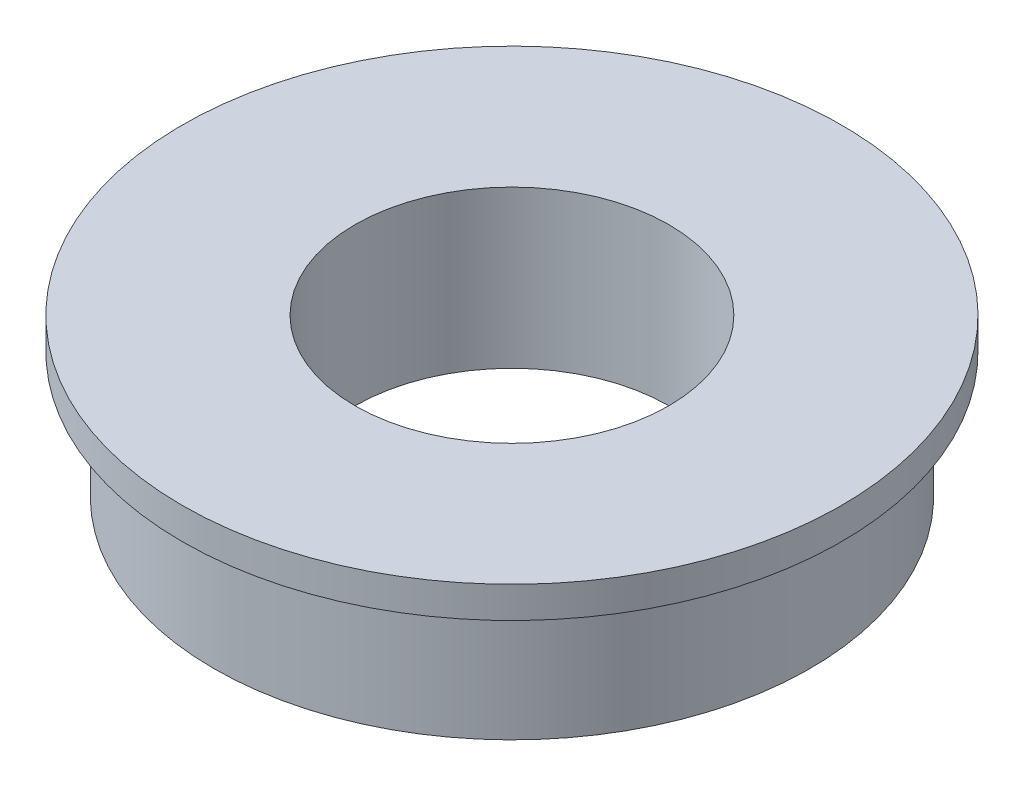
SolidWorks part; units mm, degrees
ref_plane "前视基准面" through (0, 0, 0) normal (0, 0, 1) x (1, 0, 0)
ref_plane "上视基准面" through (0, 0, 0) normal (0, 1, 0) x (1, 0, 0)
ref_plane "右视基准面" through (0, 0, 0) normal (1, 0, 0) x (0, 0, -1)
sketch "Sketch1" plane through (0, 0, 0) normal (1, 0, 0) x (0, 0, -1)
  line L0 (5, 0) -> (10.5, 0)
  line L1 (10.5, 0) -> (10.5, -1)
  line L2 (10.5, -1) -> (9.5, -1)
  line L3 (9.5, -1) -> (9.5, -5)
  line L4 (9.5, -5) -> (5, -5)
  line L5 (5, -5) -> (5, 0)
  line L6 (0, 15.0629) -> (0, -10.5262) construction
  dimension "D1" = 5
  dimension "D2" = 9.5
  dimension "D3" = 1
  dimension "D4" = 5
  dimension "D5" = 10.5
revolve "Revolve1" add sketch "Sketch1" angle 360 about L6
